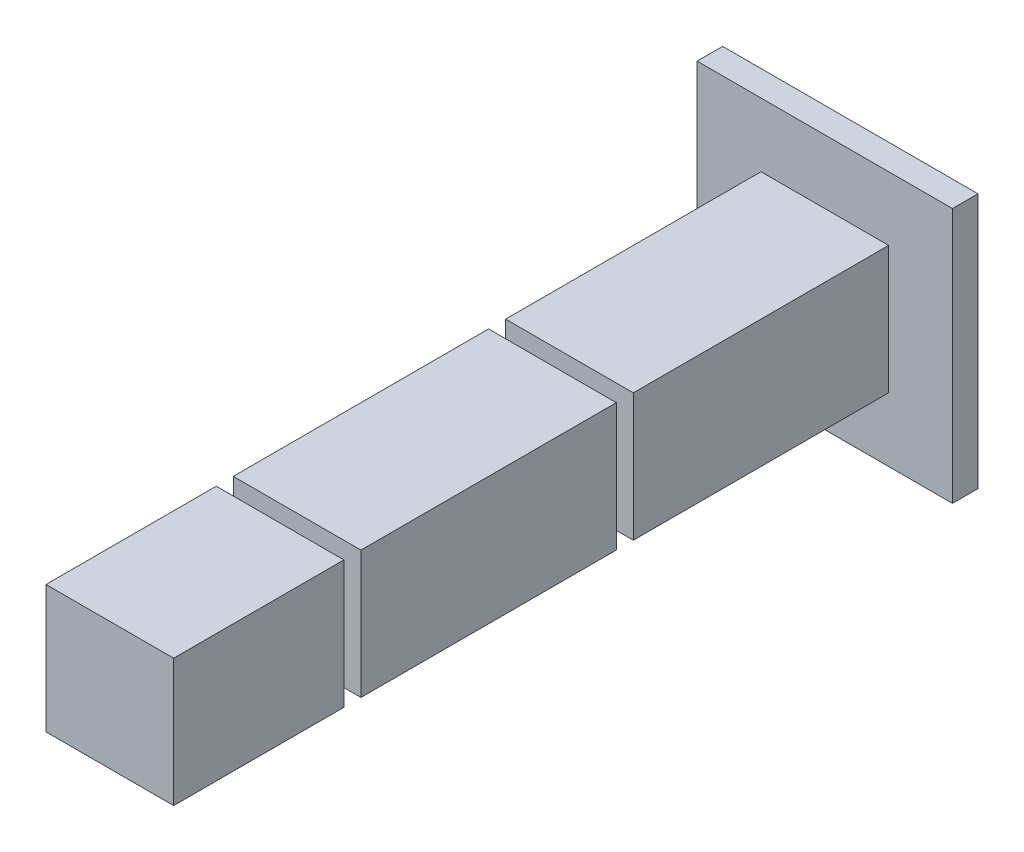
SolidWorks part; units mm, degrees
ref_plane "Front Plane" through (0, 0, 0) normal (1, 0, 0) x (0, 1, 0)
ref_plane "Top Plane" through (0, 0, 0) normal (0, 0, 1) x (0, 1, 0)
ref_plane "Right Plane" through (0, 0, 0) normal (0, 1, 0) x (-1, 0, 0)
sketch "Sketch1" plane through (0, 0, 0) normal (1, 0, 0) x (0, 1, 0)
  line L1 (-75, -7.5) -> (75, -7.5)
  line L2 (-75, -7.5) -> (-75, 7.5)
  line L3 (-75, 7.5) -> (75, 7.5)
  line L4 (75, -7.5) -> (75, 7.5)
  line L5 (-75, -7.5) -> (75, 7.5) construction
  line L6 (-75, 7.5) -> (75, -7.5) construction
  point P0 (0, 0)
  dimension "D1" = 15
  dimension "D2" = 150
extrude "Boss-Extrude1" add sketch "Sketch1" along normal blind 150
sketch "Sketch2" plane through (0, 0, 7.5) normal (0, 0, 1) x (1, 0, 0)
  line L0 (75, 75) -> (75, -75) construction
  line L1 (150, 75) -> (0, 75) construction
  line L2 (150, -75) -> (0, -75) construction
  line L4 (37.5, -37.5) -> (112.5, -37.5)
  line L5 (37.5, -37.5) -> (37.5, 37.5)
  line L6 (37.5, 37.5) -> (112.5, 37.5)
  line L7 (112.5, -37.5) -> (112.5, 37.5)
  line L8 (37.5, -37.5) -> (112.5, 37.5) construction
  line L9 (37.5, 37.5) -> (112.5, -37.5) construction
  point P6 (75, 0)
  dimension "D1" = 75
extrude "Boss-Extrude2" add sketch "Sketch2" along normal blind 150
sketch "Sketch3" plane through (0, 0, 157.5) normal (0, 0, 1) x (1, 0, 0)
  line L0 (75, 37.5) -> (75, -37.5) construction
  line L1 (112.5, 37.5) -> (37.5, 37.5) construction
  line L2 (37.5, -37.5) -> (112.5, -37.5) construction
  line L4 (60, -15) -> (90, -15)
  line L5 (60, -15) -> (60, 15)
  line L6 (60, 15) -> (90, 15)
  line L7 (90, -15) -> (90, 15)
  line L8 (60, -15) -> (90, 15) construction
  line L9 (60, 15) -> (90, -15) construction
  point P6 (75, 0)
  dimension "D1" = 30
extrude "Boss-Extrude3" add sketch "Sketch3" along normal blind 10
sketch "Sketch4" plane through (0, 0, 167.5) normal (0, 0, 1) x (1, 0, 0)
  line L0 (112.5, -37.5) -> (112.5, 37.5) construction
  line L1 (37.5, -37.5) -> (112.5, -37.5) construction
  line L2 (37.5, 37.5) -> (37.5, -37.5) construction
  line L3 (112.5, 37.5) -> (37.5, 37.5) construction
  line L4 (112.5, -37.5) -> (112.5, 37.5)
  line L5 (37.5, -37.5) -> (112.5, -37.5)
  line L6 (37.5, 37.5) -> (37.5, -37.5)
  line L7 (112.5, 37.5) -> (37.5, 37.5)
extrude "Boss-Extrude4" add sketch "Sketch4" along normal blind 150
pattern_linear "LPattern1" count 2 spacing 160 along (0, 0, 1) of "Boss-Extrude3"
sketch "Sketch5" plane through (0, 0, 327.5) normal (0, 0, 1) x (1, 0, 0)
  line L0 (37.5, 37.5) -> (37.5, -37.5) construction
  line L1 (37.5, -37.5) -> (112.5, -37.5) construction
  line L2 (112.5, -37.5) -> (112.5, 37.5) construction
  line L3 (112.5, 37.5) -> (37.5, 37.5) construction
  line L4 (37.5, 37.5) -> (37.5, -37.5)
  line L5 (37.5, -37.5) -> (112.5, -37.5)
  line L6 (112.5, -37.5) -> (112.5, 37.5)
  line L7 (112.5, 37.5) -> (37.5, 37.5)
extrude "Boss-Extrude5" add sketch "Sketch5" along normal blind 100
sketch "Sketch6" plane through (0, -37.5, 0) normal (0, -1, 0) x (1, 0, 0)
  line L1 (47.5, 337.5) -> (102.5, 337.5)
  line L2 (47.5, 337.5) -> (47.5, 427.5)
  line L3 (47.5, 427.5) -> (102.5, 427.5)
  line L4 (102.5, 337.5) -> (102.5, 427.5)
  line L5 (47.5, 337.5) -> (102.5, 427.5) construction
  line L6 (47.5, 427.5) -> (102.5, 337.5) construction
  line L9 (37.5, 427.5) -> (112.5, 427.5) construction
  line L10 (37.5, 327.5) -> (112.5, 327.5) construction
  line L11 (37.5, 427.5) -> (37.5, 327.5) construction
  point P0 (75, 382.5)
  point P5 (75, 427.5)
  dimension "D1" = 10
  dimension "D2" = 10
extrude "Cut-Extrude1" [suppressed] cut sketch "Sketch6" against normal through all
